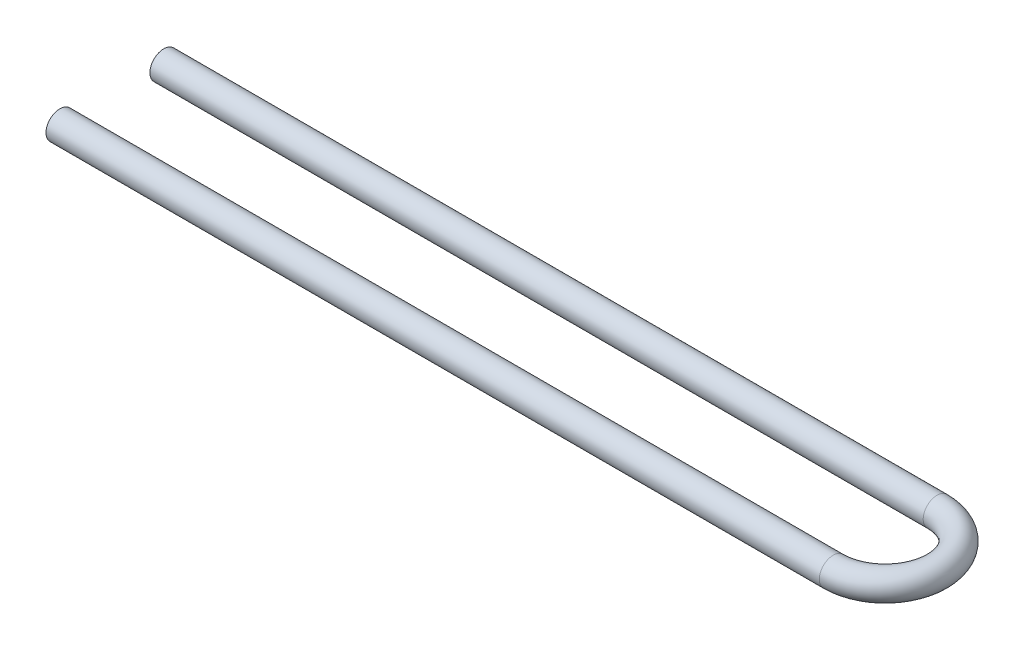
SolidWorks part; units mm, degrees
ref_plane "Спереди" through (0, 0, 0) normal (0, 0, 1) x (1, 0, 0)
ref_plane "Сверху" through (0, 0, 0) normal (0, 1, 0) x (1, 0, 0)
ref_plane "Справа" through (0, 0, 0) normal (1, 0, 0) x (0, 0, -1)
sketch "Эскиз1" plane through (0, 0, 0) normal (0, 1, 0) x (1, 0, 0)
  line L0 (55.8232, -7.5) -> (0, -7.5)
  line L1 (55.8232, 0) -> (0, 0)
  arc A0 (55.8232, -7.5) -> (55.8232, 0) centre (55.8232, -3.75) ccw
sketch "Эскиз2" plane through (0, 0, 0) normal (1, 0, 0) x (0, 0, -1)
  circle A0 centre (0, 0) radius 1
  dimension "D1" = 2
sweep "По траектории1" add profiles "Эскиз2" path "Эскиз1"
